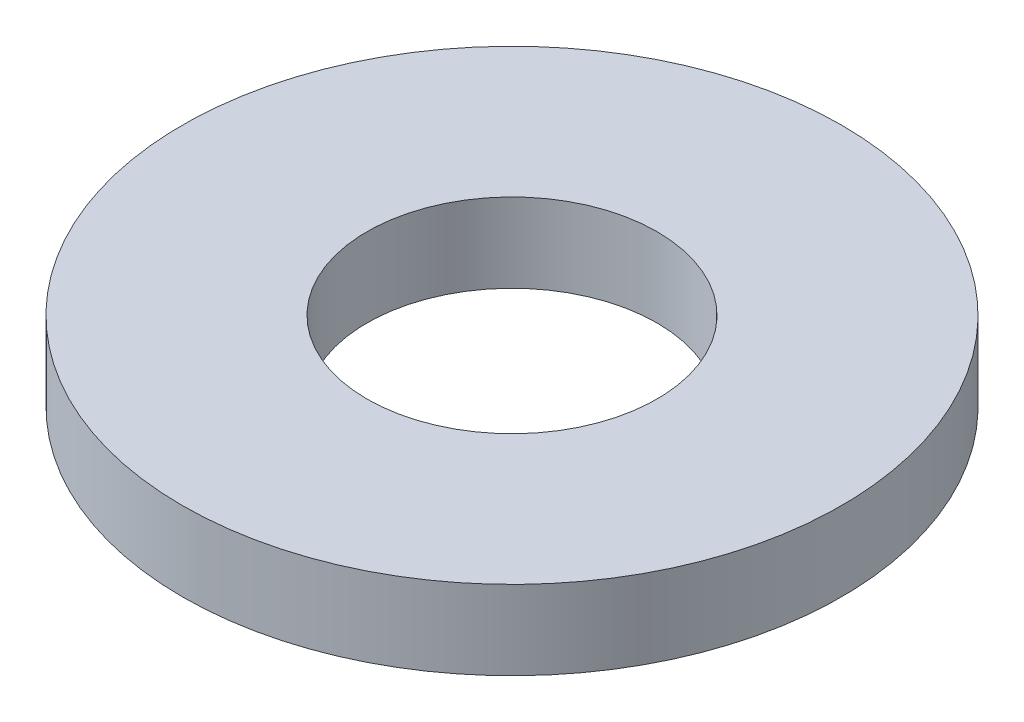
SolidWorks part; units mm, degrees
ref_plane "Přední rovina" through (0, 0, 0) normal (0, 0, 1) x (1, 0, 0)
ref_plane "Vrchní rovina" through (0, 0, 0) normal (0, 1, 0) x (1, 0, 0)
ref_plane "Pravá rovina" through (0, 0, 0) normal (1, 0, 0) x (0, 0, -1)
sketch "Skica1" plane through (0, 0, 0) normal (0, 1, 0) x (1, 0, 0)
  circle A0 centre (0, 0) radius 0.55
  circle A1 centre (0, 0) radius 1.25
  dimension "d1" = 1.1
  dimension "d2" = 2.5
extrude "Vysunout1" add sketch "Skica1" along normal blind 0.3
